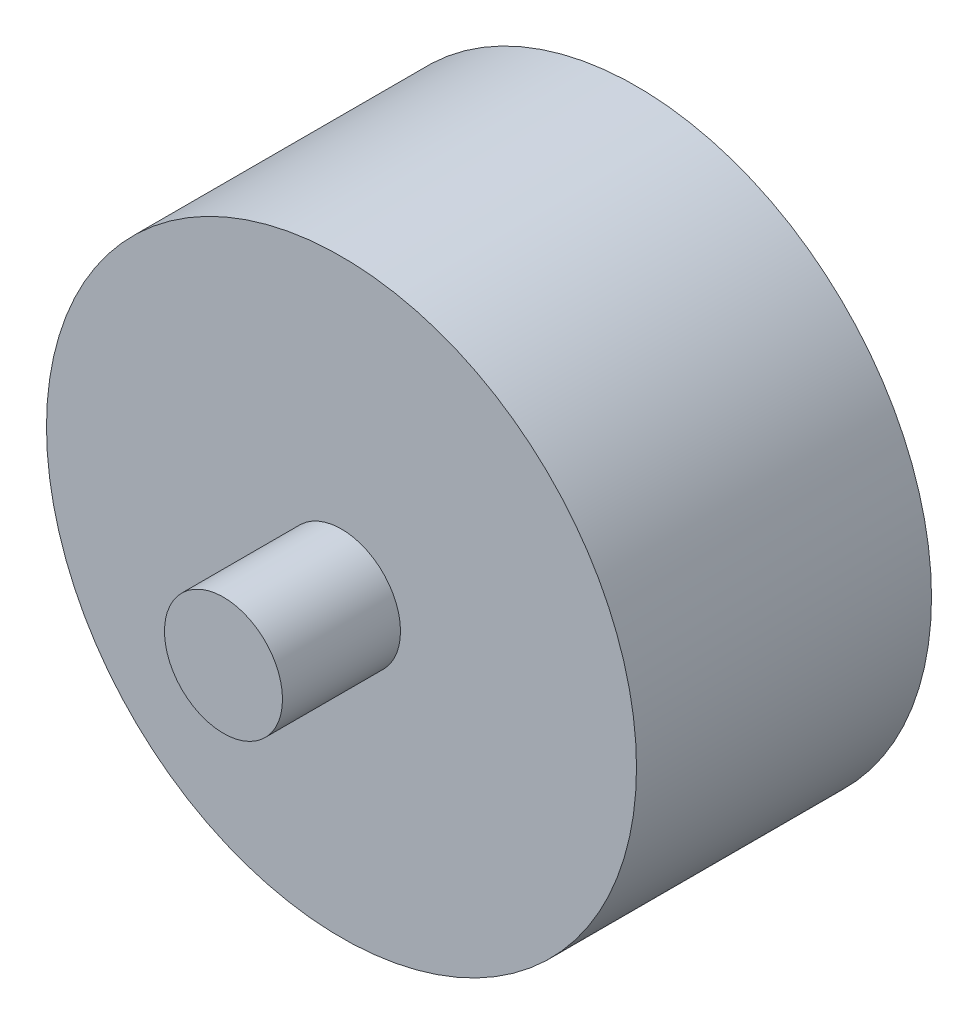
SolidWorks part; units mm, degrees
ref_plane "Front Plane" through (0, 0, 0) normal (0, 0, 1) x (1, 0, 0)
ref_plane "Top Plane" through (0, 0, 0) normal (0, 1, 0) x (1, 0, 0)
ref_plane "Right Plane" through (0, 0, 0) normal (1, 0, 0) x (0, 0, -1)
sketch "Sketch1" plane through (0, 0, 0) normal (0, 0, 1) x (1, 0, 0)
  circle A0 centre (0, 0) radius 50
  dimension "D1" = 100
extrude "Boss-Extrude1" add sketch "Sketch1" along normal mid plane 50
sketch "Sketch2" plane through (0, 0, -25) normal (0, 0, -1) x (-1, 0, 0)
  circle A0 centre (0, 0) radius 10
  dimension "D1" = 20
extrude "Boss-Extrude2" add sketch "Sketch2" along normal blind 20
sketch "Sketch3" plane through (0, 0, 25) normal (0, 0, 1) x (1, 0, 0)
  circle A0 centre (0, 0) radius 10
  dimension "D1" = 20
extrude "Boss-Extrude3" add sketch "Sketch3" along normal blind 20
